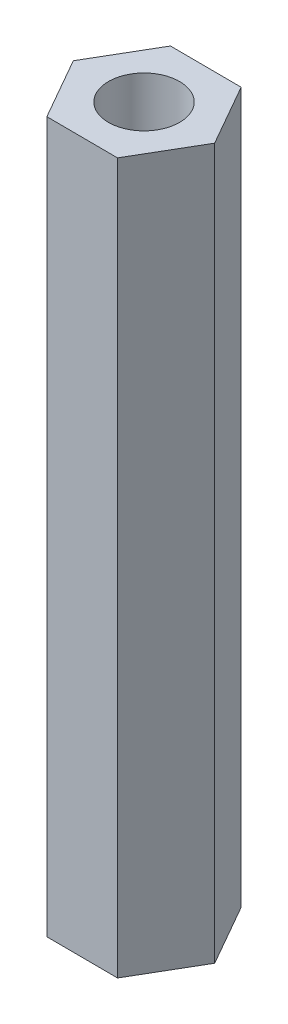
SolidWorks part; units mm, degrees
ref_plane "前视基准面" through (0, 0, 0) normal (0, 0, 1) x (1, 0, 0)
ref_plane "上视基准面" through (0, 0, 0) normal (0, 1, 0) x (1, 0, 0)
ref_plane "右视基准面" through (0, 0, 0) normal (1, 0, 0) x (0, 0, -1)
sketch "草图1" plane through (0, 0, 0) normal (0, 1, 0) x (1, 0, 0)
  line L1 (1.5132, 2.5904) -> (-1.4868, 2.6057)
  line L2 (-1.4868, 2.6057) -> (-3, 0.0153)
  line L3 (-3, 0.0153) -> (-1.5132, -2.5904)
  line L4 (-1.5132, -2.5904) -> (1.4868, -2.6057)
  line L5 (1.4868, -2.6057) -> (3, -0.0153)
  line L6 (3, -0.0153) -> (1.5132, 2.5904)
  circle A0 centre (0, 0) radius 2.5981 construction
  circle A1 centre (0, 0) radius 1.5
  dimension "D1" = 3
  dimension "D2" = 3
extrude "凸台-拉伸1" add sketch "草图1" along normal blind 30
